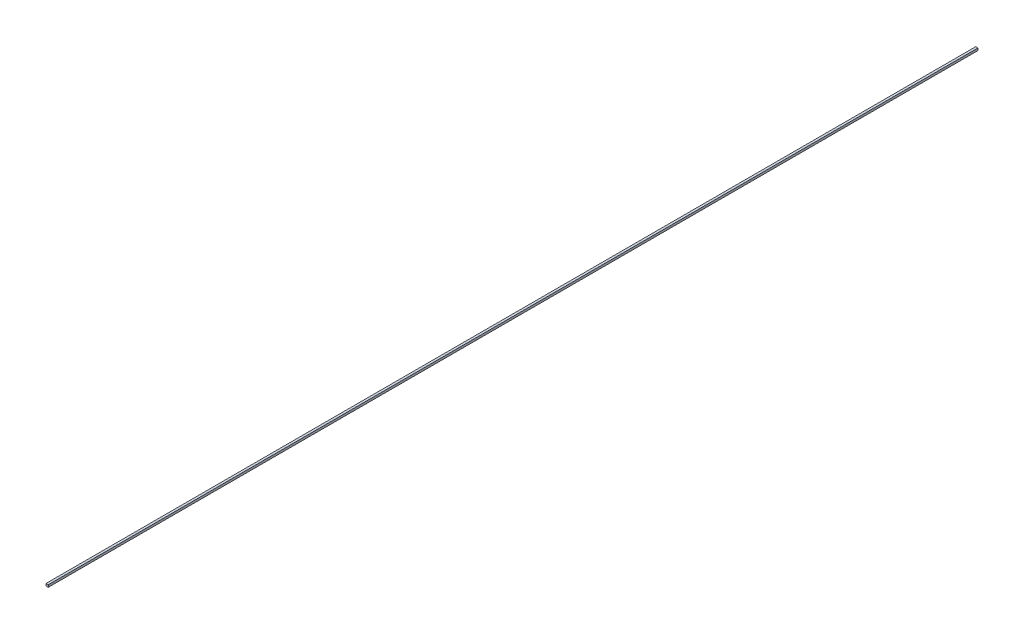
SolidWorks part; units mm, degrees
material "Birch hardwood"
ref_plane "Front Plane" through (0, 0, 0) normal (0, 0, 1) x (1, 0, 0)
ref_plane "Top Plane" through (0, 0, 0) normal (0, 1, 0) x (1, 0, 0)
ref_plane "Right Plane" through (0, 0, 0) normal (1, 0, 0) x (0, 0, -1)
sketch "Sketch1" plane through (0, 0, 0) normal (0, 0, 1) x (1, 0, 0)
  line L0 (0, 0) -> (0, 3.1608) construction
  line L1 (0, 0) -> (3.4119, 0) construction
  line L2 (3.4119, 0) -> (-3.202, 0) construction
  line L3 (-3, -3) -> (-3, 3)
  line L4 (-3, 3) -> (3, 3)
  line L5 (3, -3) -> (3, 3)
  line L6 (-3, -3) -> (3, -3)
  point P13 (0, 3)
  point P15 (3, 0)
  point P16 (-3, 0)
  dimension "D1" = 3
  dimension "D2" = 3
extrude "Boss-Extrude1" add sketch "Sketch1" along normal blind 1234.094
mirror "Mirror1" about plane through (0, 0, 0) normal (0, 0, 1) of bodies 101
